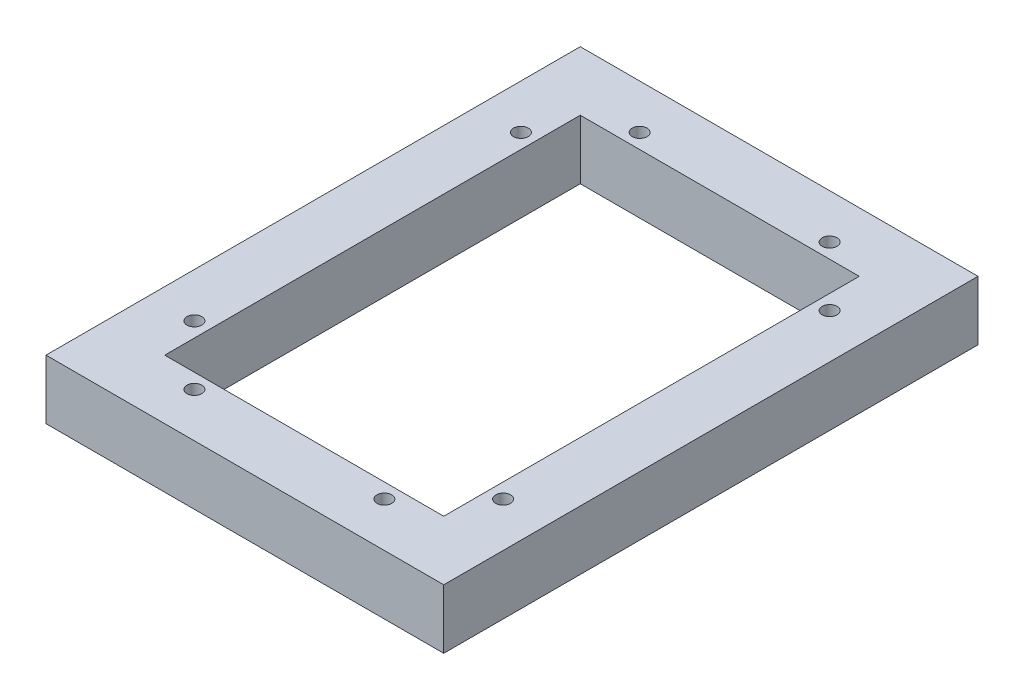
SolidWorks part; units mm, degrees
ref_plane "Front Plane" through (0, 0, 0) normal (0, 0, 1) x (1, 0, 0)
ref_plane "Top Plane" through (0, 0, 0) normal (0, 1, 0) x (1, 0, 0)
ref_plane "Right Plane" through (0, 0, 0) normal (1, 0, 0) x (0, 0, -1)
sketch "Sketch2" plane through (0, 0, 0) normal (0, 1, 0) x (1, 0, 0)
  line L1 (-85.09, -114.3) -> (85.09, -114.3)
  line L2 (-85.09, -114.3) -> (-85.09, 114.3)
  line L3 (-85.09, 114.3) -> (85.09, 114.3)
  line L4 (85.09, -114.3) -> (85.09, 114.3)
  line L5 (-85.09, -114.3) -> (85.09, 114.3) construction
  line L6 (-85.09, 114.3) -> (85.09, -114.3) construction
  line L7 (-59.69, -88.9) -> (59.69, -88.9)
  line L8 (-59.69, -88.9) -> (-59.69, 88.9)
  line L9 (-59.69, 88.9) -> (59.69, 88.9)
  line L10 (59.69, -88.9) -> (59.69, 88.9)
  line L11 (-59.69, -88.9) -> (59.69, 88.9) construction
  line L12 (-59.69, 88.9) -> (59.69, -88.9) construction
  point P0 (0, 0)
  point P6 (0, 0)
  dimension "D1" = 170.18
  dimension "D2" = 119.38
  dimension "D3" = 228.6
  dimension "D4" = 177.8
extrude "Boss-Extrude1" add sketch "Sketch2" along normal blind 25.4
sketch "Sketch3" plane through (0, 25.4, 0) normal (0, 1, 0) x (1, 0, 0)
  line L0 (-59.69, 88.9) -> (-59.69, -88.9) construction
  line L1 (59.69, 88.9) -> (-59.69, 88.9) construction
  circle A0 centre (-66.04, 69.85) radius 3.175
  circle A1 centre (-40.64, 95.25) radius 3.175
  point P4 (0, 0)
  point P5 (0, 0)
  dimension "D1" = 6.35
  dimension "D2" = 6.35
  dimension "D3" = 6.35
  dimension "D4" = 6.35
  dimension "D5" = 19.05
  dimension "D6" = 19.05
extrude "Cut-Extrude1" cut sketch "Sketch3" against normal up to next
mirror "Mirror1" about plane through (0, 0, 0) normal (1, 0, 0) of "Cut-Extrude1"
mirror "Mirror2" about plane through (0, 0, 0) normal (0, 0, 1) of "Mirror1", "Cut-Extrude1"
sketch "Sketch5" plane through (-59.69, 0, 0) normal (1, 0, 0) x (0, 0, -1)
  line L0 (88.9, 25.4) -> (88.9, 0) construction
  line L1 (88.9, 0) -> (-88.9, 0) construction
  circle A0 centre (80.01, 6.35) radius 3.175
  dimension "D1" = 6.35
  dimension "D2" = 8.89
  dimension "D3" = 6.35
